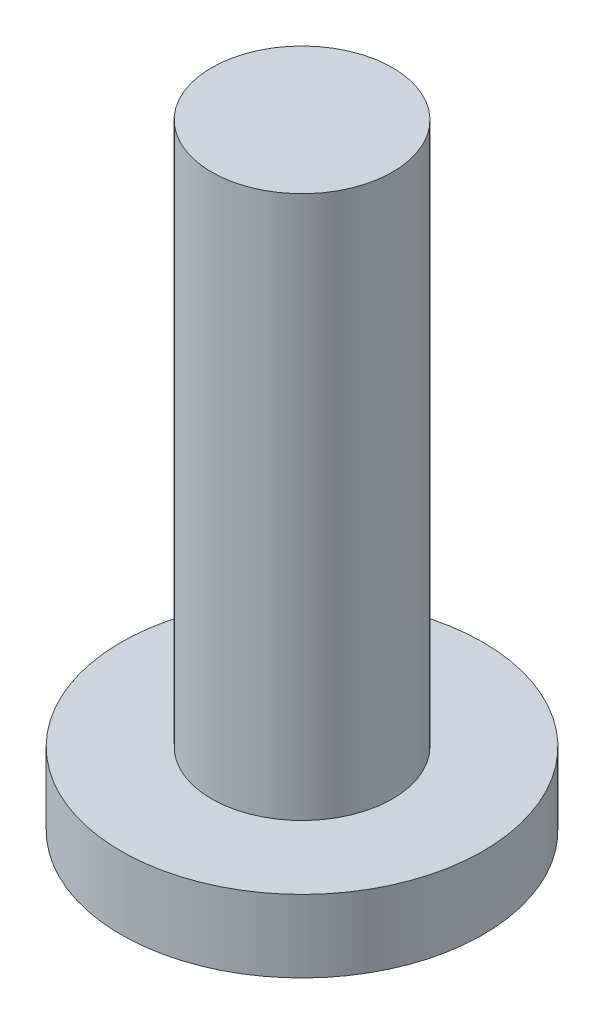
SolidWorks part; units mm, degrees
ref_plane "Plano frontal" through (0, 0, 0) normal (0, 0, 1) x (1, 0, 0)
ref_plane "Plano superior" through (0, 0, 0) normal (0, 1, 0) x (1, 0, 0)
ref_plane "Plano direito" through (0, 0, 0) normal (1, 0, 0) x (0, 0, -1)
sketch "Esboço1" plane through (0, 0, 0) normal (0, 1, 0) x (1, 0, 0)
  circle A0 centre (0, 0) radius 12.5
  dimension "D1" = 25
extrude "Ressalto-extrusão1" add sketch "Esboço1" along normal blind 75
sketch "Esboço2" plane through (0, 0, 0) normal (0, -1, 0) x (1, 0, 0)
  circle A0 centre (0, 0) radius 25
  dimension "D1" = 50
extrude "Ressalto-extrusão2" add sketch "Esboço2" along normal blind 10
